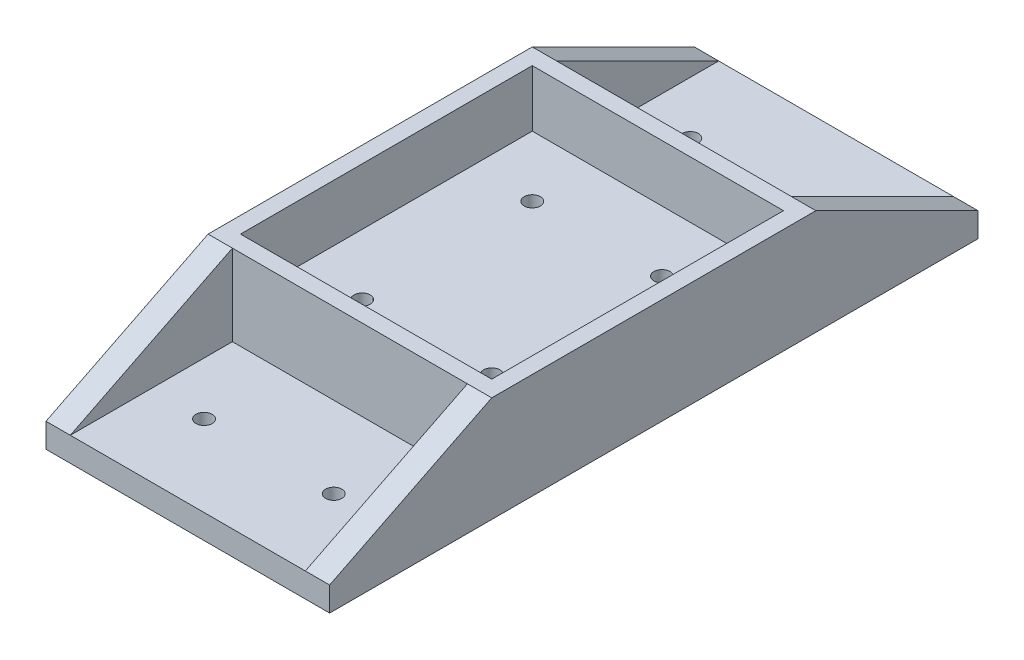
SolidWorks part; units mm, degrees
ref_plane "Front Plane" through (0, 0, 0) normal (0, 0, 1) x (1, 0, 0)
ref_plane "Top Plane" through (0, 0, 0) normal (0, 1, 0) x (1, 0, 0)
ref_plane "Right Plane" through (0, 0, 0) normal (1, 0, 0) x (0, 0, -1)
sketch "Sketch1" plane through (0, 0, 0) normal (0, 1, 0) x (1, 0, 0)
  line L0 (0, 52.6836) -> (0, -52.0341) construction
  line L1 (-86.2217, 0) -> (87.6492, 0) construction
  line L3 (-17.5, 20) -> (17.5, 20)
  line L4 (-17.5, 20) -> (-17.5, -20)
  line L5 (-17.5, -20) -> (17.5, -20)
  line L6 (17.5, 20) -> (17.5, -20)
  dimension "D1" = 35
  dimension "D2" = 40
  dimension "D3" = 17.5
  dimension "D4" = 20
extrude "Boss-Extrude1" add sketch "Sketch1" along normal blind 10
sketch "Sketch2" plane through (0, 10, 0) normal (0, 1, 0) x (1, 0, 0)
  line L0 (0, 33.3394) -> (0, -32.4091) construction
  line L1 (-43.9558, 0) -> (42.9831, 0) construction
  line L2 (17.5, -20) -> (17.5, 20) construction
  line L3 (-15.5, 18) -> (15.5, 18)
  line L4 (-15.5, 18) -> (-15.5, -18)
  line L5 (-15.5, -18) -> (15.5, -18)
  line L6 (15.5, 18) -> (15.5, -18)
  line L7 (-17.5, -20) -> (17.5, -20) construction
  dimension "D1" = 31
  dimension "D2" = 36
  dimension "D3" = 2
  dimension "D4" = 2
extrude "Cut-Extrude1" cut sketch "Sketch2" against normal blind 7
sketch "Sketch3" plane through (0, 0, 0) normal (0, -1, 0) x (1, 0, 0)
  line L0 (-17.5, 20) -> (17.5, 20) construction
  line L5 (-17.5, 40) -> (17.5, 40)
  line L6 (-17.5, 40) -> (-17.5, -40)
  line L7 (-17.5, -40) -> (17.5, -40)
  line L8 (17.5, 40) -> (17.5, -40)
  dimension "D1" = 35
  dimension "D2" = 80
  dimension "D3" = 20
extrude "Boss-Extrude2" add sketch "Sketch3" along normal blind 3
sketch "Sketch5" plane through (-17.5, 0, 0) normal (-1, 0, 0) x (0, 0, 1)
  line L0 (-20, 10) -> (-20, 0)
  line L1 (-20, 0) -> (-40, 0)
  line L2 (-40, 0) -> (-20, 10)
  line L3 (20, 10) -> (20, 0)
  line L4 (20, 0) -> (40, 0)
  line L5 (40, 0) -> (20, 10)
extrude "Boss-Extrude3" add sketch "Sketch5" against normal blind 3
mirror "Mirror1" about plane through (0, 0, 0) normal (1, 0, 0) of "Boss-Extrude3"
sketch "Sketch6" plane through (0, 3, 0) normal (0, 1, 0) x (1, 0, 0)
  line L0 (-15.5, 18) -> (-15.5, -18) construction
  line L1 (15.5, 18) -> (-15.5, 18) construction
  line L3 (15.5, -18) -> (15.5, 18) construction
  line L4 (15.5, 18) -> (-15.5, 18) construction
  line L5 (-15.5, 18) -> (-15.5, -18) construction
  line L6 (-15.5, -18) -> (15.5, -18) construction
  line L7 (-15.5, -18) -> (15.5, -18) construction
  circle A0 centre (-8, 10.5) radius 1
  circle A1 centre (8, 10.5) radius 1
  circle A2 centre (-8, -10.5) radius 1
  circle A3 centre (8, -10.5) radius 1
  point P20 (0, 0)
  dimension "D1" = 7.5
  dimension "D2" = 7.5
  dimension "D3" = 7.5
  dimension "D4" = 7.5
  dimension "D5" = 7.5
  dimension "D6" = 7.5
  dimension "D7" = 7.5
  dimension "D8" = 7.5
extrude "Cut-Extrude2" cut sketch "Sketch6" against normal blind 6
sketch "Sketch7" plane through (0, 0, 0) normal (0, 1, 0) x (1, 0, 0)
  line L0 (-14.5, 20) -> (-14.5, 40) construction
  line L1 (14.5, 40) -> (14.5, 20) construction
  line L2 (-14.5, 40) -> (14.5, 40) construction
  circle A0 centre (-8, 30) radius 1
  circle A1 centre (8, 30) radius 1
  dimension "D1" = 2
  dimension "D2" = 6.5
  dimension "D3" = 6.5
  dimension "D4" = 10
  dimension "D5" = 10
extrude "Cut-Extrude3" cut sketch "Sketch7" against normal blind 3
mirror "Mirror2" about plane through (0, 0, 0) normal (0, 0, 1) of "Cut-Extrude3"
